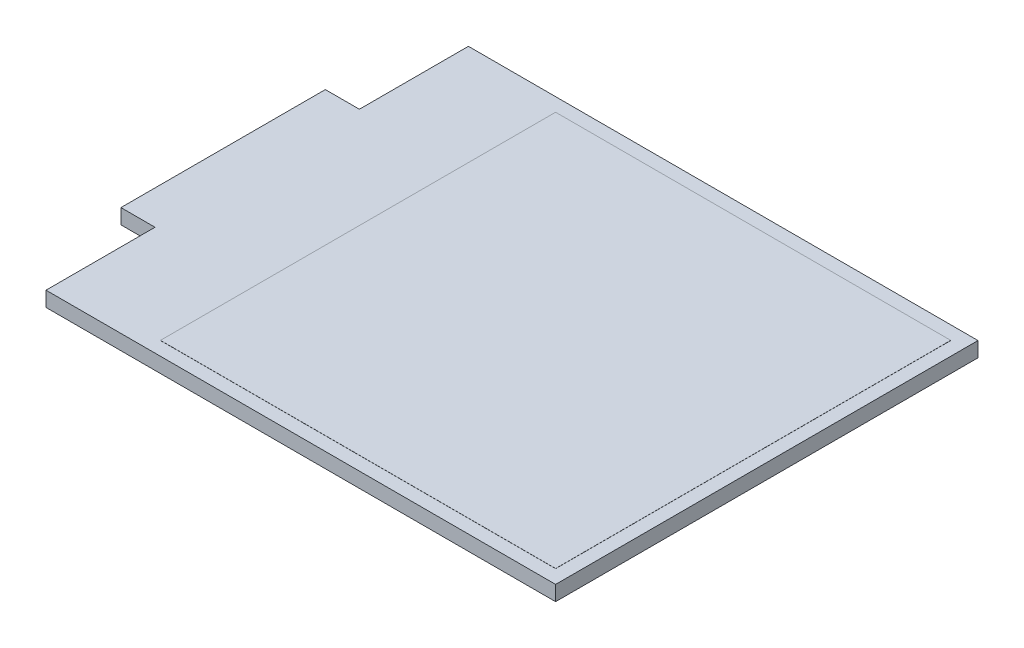
SolidWorks part; units mm, degrees
ref_plane "Face" through (0, 0, 0) normal (0, 0, 1) x (1, 0, 0)
ref_plane "Dessus" through (0, 0, 0) normal (0, 1, 0) x (1, 0, 0)
ref_plane "Droite" through (0, 0, 0) normal (1, 0, 0) x (0, 0, -1)
sketch "Sketch1" plane through (0, 0, 0) normal (0, 1, 0) x (1, 0, 0)
  line L1 (14.5, -14.5) -> (-14.5, -14.5)
  line L2 (14.5, -14.5) -> (14.5, 14.5)
  line L3 (14.5, 14.5) -> (-14.5, 14.5)
  line L4 (-14.5, -14.5) -> (-14.5, 14.5)
  line L5 (14.5, -14.5) -> (-14.5, 14.5) construction
  line L6 (14.5, 14.5) -> (-14.5, -14.5) construction
  point P0 (0, 0)
  dimension "D1" = 29
extrude "Boss-Extrude1" add sketch "Sketch1" along normal blind 0.01
sketch "Sketch2" plane through (0, 0, 0) normal (0, -1, 0) x (1, 0, 0)
  line L0 (-21.9, 15.5) -> (-21.9, 7.5)
  line L1 (-21.9, -15.5) -> (15.5, -15.5)
  line L2 (15.5, -15.5) -> (15.5, 15.5)
  line L3 (15.5, 15.5) -> (-21.9, 15.5)
  line L4 (14.5, 14.5) -> (14.5, 15.5) construction
  line L5 (14.5, -14.5) -> (15.5, -14.5) construction
  line L6 (-14.5, -14.5) -> (-14.5, -15.5) construction
  line L7 (0, 0) -> (15.5, 0) construction
  line L8 (-21.9, 7.5) -> (-24.4, 7.5)
  line L9 (-24.4, 7.5) -> (-24.4, -7.5)
  line L10 (-24.4, -7.5) -> (-21.9, -7.5)
  line L11 (0, 0) -> (-24.4, 0) construction
  line L12 (-21.9, -7.5) -> (-21.9, -15.5)
  dimension "D1" = 31
  dimension "D2" = 37.4
  dimension "D3" = 2.5
  dimension "D4" = 15
extrude "Boss-Extrude2" add sketch "Sketch2" along normal blind 1.1
